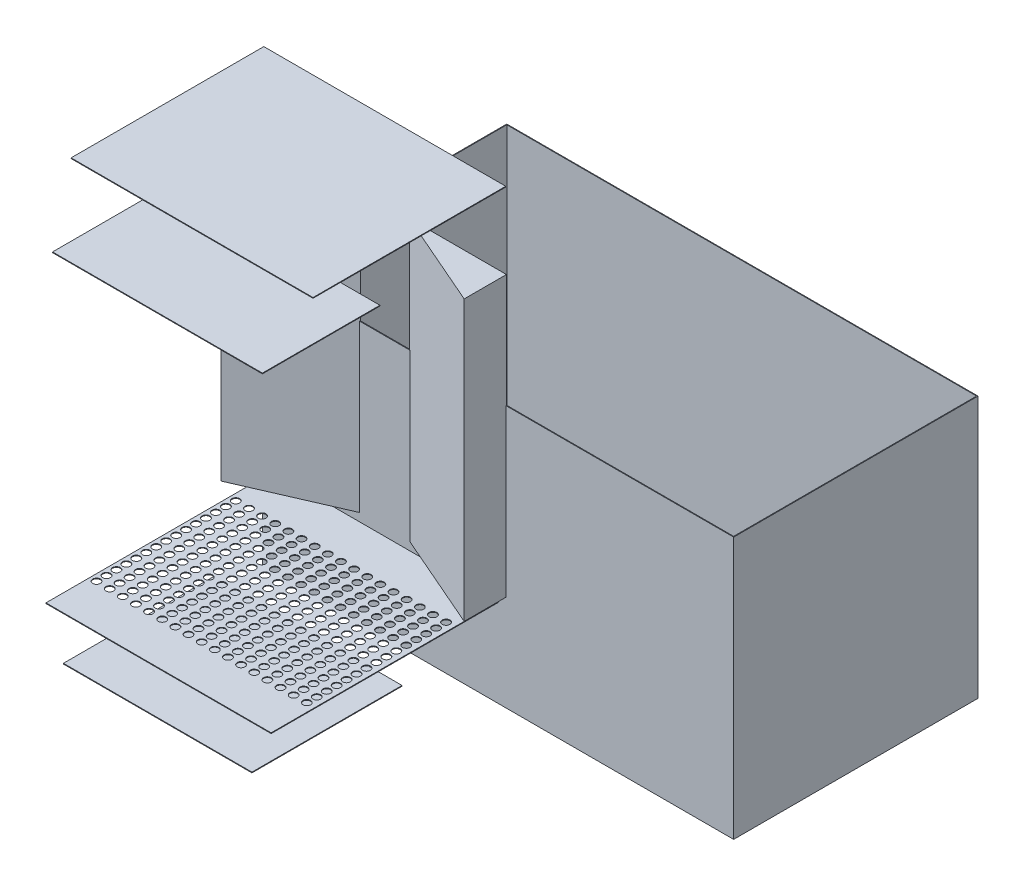
SolidWorks part; units mm, degrees
ref_plane "Спереди" through (0, 0, 0) normal (0, 0, 1) x (1, 0, 0)
ref_plane "Сверху" through (0, 0, 0) normal (0, 1, 0) x (1, 0, 0)
ref_plane "Справа" through (0, 0, 0) normal (1, 0, 0) x (0, 0, -1)
sketch "MASTER_FOOTPRINT" plane through (0, 0, 0) normal (0, 1, 0) x (1, 0, 0)
  line L1 (0, 0) -> (1350, 0)
  line L2 (0, 0) -> (0, 700)
  line L3 (0, 700) -> (1350, 700)
  line L4 (1350, 0) -> (1350, 700)
  dimension "D1" = 1350
  dimension "D2" = 700
extrude "BATH_BASE_PLATE" add sketch "MASTER_FOOTPRINT" along normal blind 750
shell "BATH_SHELL_2MM" thickness 2
sketch "Эскиз1" plane through (0, 0, 0) normal (0, 1, 0) x (1, 0, 0)
  line L1 (80, -220) -> (620, -220)
  line L2 (80, -220) -> (80, -650)
  line L3 (80, -650) -> (620, -650)
  line L4 (620, -220) -> (620, -650)
extrude "INLET_IMPACT_BAFFLE" add sketch "Эскиз1" along normal blind 2 from offset 125 separate body
sketch "Эскиз2" plane through (0, 0, 0) normal (0, 1, 0) x (1, 0, 0)
  line L0 (2, 2) -> (1348, 2) construction
  line L1 (30, 2) -> (675, 2)
  line L2 (30, 2) -> (30, -650)
  line L3 (30, -650) -> (675, -650)
  line L4 (675, 2) -> (675, -650)
  circle A0 centre (48.8235, -125) radius 11
  circle A1 centre (48.8235, -153.5) radius 11
  circle A2 centre (48.8235, -182) radius 11
  circle A3 centre (48.8235, -210.5) radius 11
  circle A4 centre (48.8235, -239) radius 11
  circle A5 centre (48.8235, -267.5) radius 11
  circle A6 centre (48.8235, -296) radius 11
  circle A7 centre (48.8235, -324.5) radius 11
  circle A8 centre (48.8235, -353) radius 11
  circle A9 centre (48.8235, -381.5) radius 11
  circle A10 centre (48.8235, -410) radius 11
  circle A11 centre (48.8235, -438.5) radius 11
  circle A12 centre (48.8235, -467) radius 11
  circle A13 centre (48.8235, -495.5) radius 11
  circle A14 centre (48.8235, -524) radius 11
  circle A15 centre (86.4706, -125) radius 11
  circle A16 centre (86.4706, -153.5) radius 11
  circle A17 centre (86.4706, -182) radius 11
  circle A18 centre (86.4706, -210.5) radius 11
  circle A19 centre (86.4706, -239) radius 11
  circle A20 centre (86.4706, -267.5) radius 11
  circle A21 centre (86.4706, -296) radius 11
  circle A22 centre (86.4706, -324.5) radius 11
  circle A23 centre (86.4706, -353) radius 11
  circle A24 centre (86.4706, -381.5) radius 11
  circle A25 centre (86.4706, -410) radius 11
  circle A26 centre (86.4706, -438.5) radius 11
  circle A27 centre (86.4706, -467) radius 11
  circle A28 centre (86.4706, -495.5) radius 11
  circle A29 centre (86.4706, -524) radius 11
  circle A30 centre (124.1176, -125) radius 11
  circle A31 centre (124.1176, -153.5) radius 11
  circle A32 centre (124.1176, -182) radius 11
  circle A33 centre (124.1176, -210.5) radius 11
  circle A34 centre (124.1176, -239) radius 11
  circle A35 centre (124.1176, -267.5) radius 11
  circle A36 centre (124.1176, -296) radius 11
  circle A37 centre (124.1176, -324.5) radius 11
  circle A38 centre (124.1176, -353) radius 11
  circle A39 centre (124.1176, -381.5) radius 11
  circle A40 centre (124.1176, -410) radius 11
  circle A41 centre (124.1176, -438.5) radius 11
  circle A42 centre (124.1176, -467) radius 11
  circle A43 centre (124.1176, -495.5) radius 11
  circle A44 centre (124.1176, -524) radius 11
  circle A45 centre (161.7647, -125) radius 11
  circle A46 centre (161.7647, -153.5) radius 11
  circle A47 centre (161.7647, -182) radius 11
  circle A48 centre (161.7647, -210.5) radius 11
  circle A49 centre (161.7647, -239) radius 11
  circle A50 centre (161.7647, -267.5) radius 11
  circle A51 centre (161.7647, -296) radius 11
  circle A52 centre (161.7647, -324.5) radius 11
  circle A53 centre (161.7647, -353) radius 11
  circle A54 centre (161.7647, -381.5) radius 11
  circle A55 centre (161.7647, -410) radius 11
  circle A56 centre (161.7647, -438.5) radius 11
  circle A57 centre (161.7647, -467) radius 11
  circle A58 centre (161.7647, -495.5) radius 11
  circle A59 centre (161.7647, -524) radius 11
  circle A60 centre (199.4118, -125) radius 11
  circle A61 centre (199.4118, -153.5) radius 11
  circle A62 centre (199.4118, -182) radius 11
  circle A63 centre (199.4118, -210.5) radius 11
  circle A64 centre (199.4118, -239) radius 11
  circle A65 centre (199.4118, -267.5) radius 11
  circle A66 centre (199.4118, -296) radius 11
  circle A67 centre (199.4118, -324.5) radius 11
  circle A68 centre (199.4118, -353) radius 11
  circle A69 centre (199.4118, -381.5) radius 11
  circle A70 centre (199.4118, -410) radius 11
  circle A71 centre (199.4118, -438.5) radius 11
  circle A72 centre (199.4118, -467) radius 11
  circle A73 centre (199.4118, -495.5) radius 11
  circle A74 centre (199.4118, -524) radius 11
  circle A75 centre (237.0588, -125) radius 11
  circle A76 centre (237.0588, -153.5) radius 11
  circle A77 centre (237.0588, -182) radius 11
  circle A78 centre (237.0588, -210.5) radius 11
  circle A79 centre (237.0588, -239) radius 11
  circle A80 centre (237.0588, -267.5) radius 11
  circle A81 centre (237.0588, -296) radius 11
  circle A82 centre (237.0588, -324.5) radius 11
  circle A83 centre (237.0588, -353) radius 11
  circle A84 centre (237.0588, -381.5) radius 11
  circle A85 centre (237.0588, -410) radius 11
  circle A86 centre (237.0588, -438.5) radius 11
  circle A87 centre (237.0588, -467) radius 11
  circle A88 centre (237.0588, -495.5) radius 11
  circle A89 centre (237.0588, -524) radius 11
  circle A90 centre (274.7059, -125) radius 11
  circle A91 centre (274.7059, -153.5) radius 11
  circle A92 centre (274.7059, -182) radius 11
  circle A93 centre (274.7059, -210.5) radius 11
  circle A94 centre (274.7059, -239) radius 11
  circle A95 centre (274.7059, -267.5) radius 11
  circle A96 centre (274.7059, -296) radius 11
  circle A97 centre (274.7059, -324.5) radius 11
  circle A98 centre (274.7059, -353) radius 11
  circle A99 centre (274.7059, -381.5) radius 11
  circle A100 centre (274.7059, -410) radius 11
  circle A101 centre (274.7059, -438.5) radius 11
  circle A102 centre (274.7059, -467) radius 11
  circle A103 centre (274.7059, -495.5) radius 11
  circle A104 centre (274.7059, -524) radius 11
  circle A105 centre (312.3529, -125) radius 11
  circle A106 centre (312.3529, -153.5) radius 11
  circle A107 centre (312.3529, -182) radius 11
  circle A108 centre (312.3529, -210.5) radius 11
  circle A109 centre (312.3529, -239) radius 11
  circle A110 centre (312.3529, -267.5) radius 11
  circle A111 centre (312.3529, -296) radius 11
  circle A112 centre (312.3529, -324.5) radius 11
  circle A113 centre (312.3529, -353) radius 11
  circle A114 centre (312.3529, -381.5) radius 11
  circle A115 centre (312.3529, -410) radius 11
  circle A116 centre (312.3529, -438.5) radius 11
  circle A117 centre (312.3529, -467) radius 11
  circle A118 centre (312.3529, -495.5) radius 11
  circle A119 centre (312.3529, -524) radius 11
  circle A120 centre (350, -125) radius 11
  circle A121 centre (350, -153.5) radius 11
  circle A122 centre (350, -182) radius 11
  circle A123 centre (350, -210.5) radius 11
  circle A124 centre (350, -239) radius 11
  circle A125 centre (350, -267.5) radius 11
  circle A126 centre (350, -296) radius 11
  circle A127 centre (350, -324.5) radius 11
  circle A128 centre (350, -353) radius 11
  circle A129 centre (350, -381.5) radius 11
  circle A130 centre (350, -410) radius 11
  circle A131 centre (350, -438.5) radius 11
  circle A132 centre (350, -467) radius 11
  circle A133 centre (350, -495.5) radius 11
  circle A134 centre (350, -524) radius 11
  circle A135 centre (387.6471, -125) radius 11
  circle A136 centre (387.6471, -153.5) radius 11
  circle A137 centre (387.6471, -182) radius 11
  circle A138 centre (387.6471, -210.5) radius 11
  circle A139 centre (387.6471, -239) radius 11
  circle A140 centre (387.6471, -267.5) radius 11
  circle A141 centre (387.6471, -296) radius 11
  circle A142 centre (387.6471, -324.5) radius 11
  circle A143 centre (387.6471, -353) radius 11
  circle A144 centre (387.6471, -381.5) radius 11
  circle A145 centre (387.6471, -410) radius 11
  circle A146 centre (387.6471, -438.5) radius 11
  circle A147 centre (387.6471, -467) radius 11
  circle A148 centre (387.6471, -495.5) radius 11
  circle A149 centre (387.6471, -524) radius 11
  circle A150 centre (425.2941, -125) radius 11
  circle A151 centre (425.2941, -153.5) radius 11
  circle A152 centre (425.2941, -182) radius 11
  circle A153 centre (425.2941, -210.5) radius 11
  circle A154 centre (425.2941, -239) radius 11
  circle A155 centre (425.2941, -267.5) radius 11
  circle A156 centre (425.2941, -296) radius 11
  circle A157 centre (425.2941, -324.5) radius 11
  circle A158 centre (425.2941, -353) radius 11
  circle A159 centre (425.2941, -381.5) radius 11
  circle A160 centre (425.2941, -410) radius 11
  circle A161 centre (425.2941, -438.5) radius 11
  circle A162 centre (425.2941, -467) radius 11
  circle A163 centre (425.2941, -495.5) radius 11
  circle A164 centre (425.2941, -524) radius 11
  circle A165 centre (462.9412, -125) radius 11
  circle A166 centre (462.9412, -153.5) radius 11
  circle A167 centre (462.9412, -182) radius 11
  circle A168 centre (462.9412, -210.5) radius 11
  circle A169 centre (462.9412, -239) radius 11
  circle A170 centre (462.9412, -267.5) radius 11
  circle A171 centre (462.9412, -296) radius 11
  circle A172 centre (462.9412, -324.5) radius 11
  circle A173 centre (462.9412, -353) radius 11
  circle A174 centre (462.9412, -381.5) radius 11
  circle A175 centre (462.9412, -410) radius 11
  circle A176 centre (462.9412, -438.5) radius 11
  circle A177 centre (462.9412, -467) radius 11
  circle A178 centre (462.9412, -495.5) radius 11
  circle A179 centre (462.9412, -524) radius 11
  circle A180 centre (500.5882, -125) radius 11
  circle A181 centre (500.5882, -153.5) radius 11
  circle A182 centre (500.5882, -182) radius 11
  circle A183 centre (500.5882, -210.5) radius 11
  circle A184 centre (500.5882, -239) radius 11
  circle A185 centre (500.5882, -267.5) radius 11
  circle A186 centre (500.5882, -296) radius 11
  circle A187 centre (500.5882, -324.5) radius 11
  circle A188 centre (500.5882, -353) radius 11
  circle A189 centre (500.5882, -381.5) radius 11
  circle A190 centre (500.5882, -410) radius 11
  circle A191 centre (500.5882, -438.5) radius 11
  circle A192 centre (500.5882, -467) radius 11
  circle A193 centre (500.5882, -495.5) radius 11
  circle A194 centre (500.5882, -524) radius 11
  circle A195 centre (538.2353, -125) radius 11
  circle A196 centre (538.2353, -153.5) radius 11
  circle A197 centre (538.2353, -182) radius 11
  circle A198 centre (538.2353, -210.5) radius 11
  circle A199 centre (538.2353, -239) radius 11
  circle A200 centre (538.2353, -267.5) radius 11
  circle A201 centre (538.2353, -296) radius 11
  circle A202 centre (538.2353, -324.5) radius 11
  circle A203 centre (538.2353, -353) radius 11
  circle A204 centre (538.2353, -381.5) radius 11
  circle A205 centre (538.2353, -410) radius 11
  circle A206 centre (538.2353, -438.5) radius 11
  circle A207 centre (538.2353, -467) radius 11
  circle A208 centre (538.2353, -495.5) radius 11
  circle A209 centre (538.2353, -524) radius 11
  circle A210 centre (575.8824, -125) radius 11
  circle A211 centre (575.8824, -153.5) radius 11
  circle A212 centre (575.8824, -182) radius 11
  circle A213 centre (575.8824, -210.5) radius 11
  circle A214 centre (575.8824, -239) radius 11
  circle A215 centre (575.8824, -267.5) radius 11
  circle A216 centre (575.8824, -296) radius 11
  circle A217 centre (575.8824, -324.5) radius 11
  circle A218 centre (575.8824, -353) radius 11
  circle A219 centre (575.8824, -381.5) radius 11
  circle A220 centre (575.8824, -410) radius 11
  circle A221 centre (575.8824, -438.5) radius 11
  circle A222 centre (575.8824, -467) radius 11
  circle A223 centre (575.8824, -495.5) radius 11
  circle A224 centre (575.8824, -524) radius 11
  circle A225 centre (613.5294, -125) radius 11
  circle A226 centre (613.5294, -153.5) radius 11
  circle A227 centre (613.5294, -182) radius 11
  circle A228 centre (613.5294, -210.5) radius 11
  circle A229 centre (613.5294, -239) radius 11
  circle A230 centre (613.5294, -267.5) radius 11
  circle A231 centre (613.5294, -296) radius 11
  circle A232 centre (613.5294, -324.5) radius 11
  circle A233 centre (613.5294, -353) radius 11
  circle A234 centre (613.5294, -381.5) radius 11
  circle A235 centre (613.5294, -410) radius 11
  circle A236 centre (613.5294, -438.5) radius 11
  circle A237 centre (613.5294, -467) radius 11
  circle A238 centre (613.5294, -495.5) radius 11
  circle A239 centre (613.5294, -524) radius 11
  circle A240 centre (651.1765, -125) radius 11
  circle A241 centre (651.1765, -153.5) radius 11
  circle A242 centre (651.1765, -182) radius 11
  circle A243 centre (651.1765, -210.5) radius 11
  circle A244 centre (651.1765, -239) radius 11
  circle A245 centre (651.1765, -267.5) radius 11
  circle A246 centre (651.1765, -296) radius 11
  circle A247 centre (651.1765, -324.5) radius 11
  circle A248 centre (651.1765, -353) radius 11
  circle A249 centre (651.1765, -381.5) radius 11
  circle A250 centre (651.1765, -410) radius 11
  circle A251 centre (651.1765, -438.5) radius 11
  circle A252 centre (651.1765, -467) radius 11
  circle A253 centre (651.1765, -495.5) radius 11
  circle A254 centre (651.1765, -524) radius 11
extrude "DISTRIBUTOR_D22" add sketch "Эскиз2" along normal blind 2 from offset 250 separate body
sketch "Эскиз3" plane through (0, 0, 0) normal (0, 1, 0) x (1, 0, 0)
  line L0 (30, -650) -> (675, -650) construction
  line L1 (48.8235, -313.5) -> (650, -313.5)
  line L2 (48.8235, -313.5) -> (48.8235, -650)
  line L3 (48.8235, -650) -> (650, -650)
  line L4 (650, -313.5) -> (650, -650)
  circle A0 centre (48.8235, -324.5) radius 11 construction
extrude "OUTLET_SUBMERGED_BAFFLE" add sketch "Эскиз3" along normal blind 2 from offset 1130 separate body
sketch "Эскиз4" plane through (0, 0, 0) normal (0, 1, 0) x (1, 0, 0)
  line L1 (2, 2) -> (695, 2)
  line L2 (2, 2) -> (2, -550)
  line L3 (2, -550) -> (695, -550)
  line L4 (695, 2) -> (695, -550)
extrude "OVERFLOW_WEIR_Z550" add sketch "Эскиз4" along normal blind 2 from offset 1290 separate body
sketch "Эскиз5" plane through (0, 0, 0) normal (0, 1, 0) x (1, 0, 0)
  line L0 (2, 1) -> (2, -120)
  line L1 (2, -120) -> (280, 1)
  line L2 (280, 1) -> (2, 1)
  line L3 (698, 1) -> (698, -120)
  line L4 (698, -120) -> (420, 1)
  line L5 (420, 1) -> (698, 1)
extrude "SLOPED_SEDIMENT_FLOOR" add sketch "Эскиз5" along normal blind 800 from offset 275
sketch3d "SCREW_AXIS_30DEG_REFERENCE"
  line L0 (350, 400, 70) -> (350, 1450, 676.2178)
sketch "Эскиз6" plane through (0, 125, 0) normal (0, -1, 0) x (1, 0, 0)
  circle A0 centre (350, -420) radius 50
equation "\"AI_Q_Peak\"= 0.006"
equation "\"AI_B_Bath\"= 700"
equation "\"AI_L_Settle\"= 900"
equation "\"AI_L_Inlet\"= 250"
equation "\"AI_L_Outlet\"= 200"
equation "\"AI_L_Bath\"= 1350"
equation "\"AI_H_Water\"= 550"
equation "\"AI_H_Freeboard\"= 200"
equation "\"AI_H_Bath\"= 750"
equation "\"AI_Shell_Thickness\"= 2"
equation "\"AI_Inlet_DN\"= 100"
equation "\"AI_Weir_Width\"= 600"
equation "\"AI_Inlet_Baffle_Offset\"= 125"
equation "\"AI_Distributor_Open_Area\"= 0.28"
equation "\"AI_Distributor_Hole_Dia\"= 22"
equation "\"AI_Distributor_Blind_Zone\"= 110"
equation "\"AI_Outlet_Baffle_Depth\"= 250"
equation "\"AI_Screw_Diameter\"= 100"
equation "\"AI_Screw_Pitch\"= 100"
equation "\"AI_Screw_Angle\"= 30"
equation "\"AI_Screw_Rpm\"= 15"
equation "\"AI_Screw_Clearance\"= 5"
equation "\"AI_Liner_Thickness\"= 5"
equation "\"AI_Discharge_Height\"= 650"
equation "\"AI_Frame_Height\"= 500"
equation "\"D1@MASTER_FOOTPRINT\" = \"AI_L_Bath\""
equation "\"D2@MASTER_FOOTPRINT\" = \"AI_B_Bath\""
equation "\"D1@BATH_BASE_PLATE\" = \"AI_H_Bath\""
